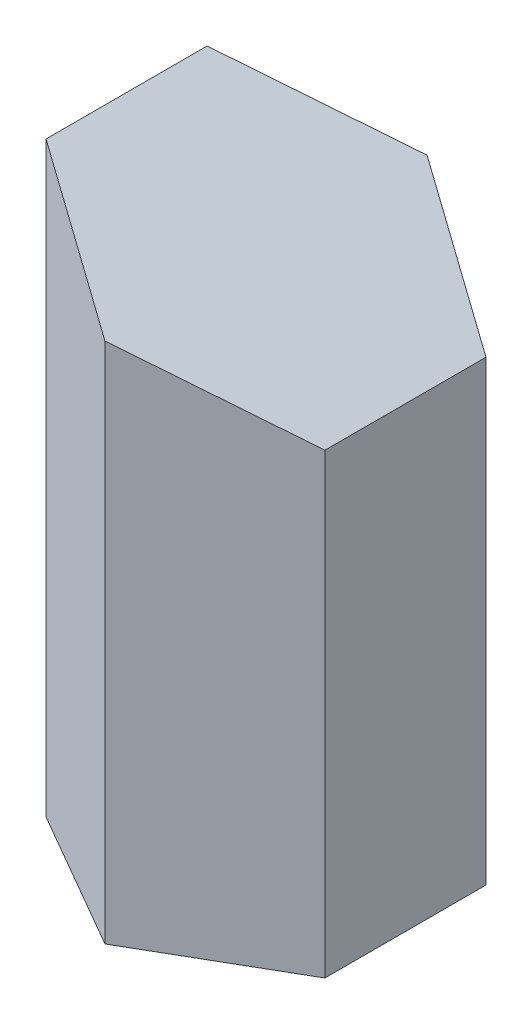
SolidWorks part; units mm, degrees
ref_plane "Front Plane" through (0, 0, 0) normal (0, 0, 1) x (1, 0, 0)
ref_plane "Top Plane" through (0, 0, 0) normal (0, 1, 0) x (1, 0, 0)
ref_plane "Right Plane" through (0, 0, 0) normal (1, 0, 0) x (0, 0, -1)
sketch "Sketch1" plane through (0, 0, 0) normal (0, 1, 0) x (1, 0, 0)
  line L1 (0, -10.9697) -> (9.5, -5.4848)
  line L2 (9.5, -5.4848) -> (9.5, 5.4848)
  line L3 (9.5, 5.4848) -> (0, 10.9697)
  line L4 (0, 10.9697) -> (-9.5, 5.4848)
  line L5 (-9.5, 5.4848) -> (-9.5, -5.4848)
  line L6 (-9.5, -5.4848) -> (0, -10.9697)
  circle A0 centre (0, 0) radius 9.5 construction
  point P1 (0, 0)
  point P10 (0, 0)
  dimension "D1" = 19
extrude "Boss-Extrude1" add sketch "Sketch1" along normal blind 40
sketch "Sketch2" plane through (0, 0, 0) normal (0, 0, 1) x (1, 0, 0)
  line L0 (-9.5, 40) -> (9.5, 31.1402)
  line L1 (-9.5, 40) -> (-9.5, 0) construction
  line L2 (-9.5, 40) -> (0, 40) construction
  line L3 (9.5, 40) -> (9.5, 0) construction
  line L4 (0, 40) -> (9.5, 40) construction
  line L5 (9.5, 31.1402) -> (9.5, 40)
  line L6 (9.5, 40) -> (-9.5, 40)
  dimension "D1" = 25
extrude "Cut-Extrude1" cut sketch "Sketch2" against normal through all both and the other way through all
